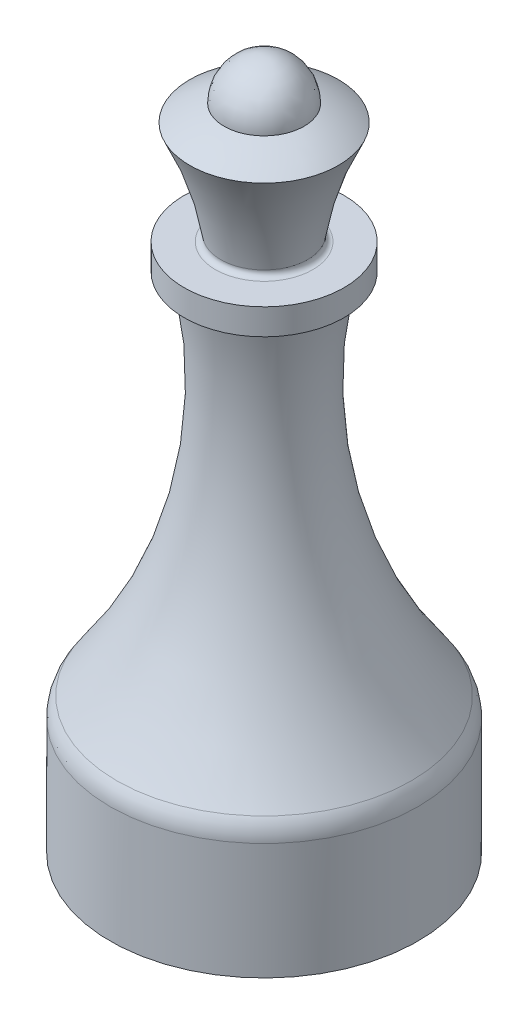
SolidWorks part; units mm, degrees
ref_plane "Front Plane" through (0, 0, 0) normal (0, 0, 1) x (1, 0, 0)
ref_plane "Top Plane" through (0, 0, 0) normal (0, 1, 0) x (1, 0, 0)
ref_plane "Right Plane" through (0, 0, 0) normal (1, 0, 0) x (0, 0, -1)
sketch "Sketch1" plane through (0, 0, 0) normal (0, 0, 1) x (1, 0, 0)
  line L6 (0, 0) -> (14.5, 0)
  line L7 (9.5, 0) -> (9.5, 12)
  line L8 (14.5, 0) -> (14.5, 12)
  line L9 (45.1511, 65) -> (-46.8975, 65) construction
  line L13 (0, 0) -> (0, 65)
  line L14 (8.0064, 17.2031) -> (0, 30)
  line L15 (9.5, 12) -> (14.5, 12) construction
  arc A5 (14.5, 12) -> (6, 46.5615) centre (47.7654, 38.5072) cw
  arc A6 (9.5, 12) -> (8.0064, 17.2031) centre (-0.3099, 12) ccw
  line B0 (6, 46.5615) -> (7.5366, 47.396)
  line B1 (7.5366, 47.396) -> (7.5366, 49.844)
  line B2 (7.5366, 49.844) -> (4.0161, 49.844)
  arc B3 (4.0161, 49.844) -> (7.0059, 59.5593) centre (33.8306, 45.9865) cw
  arc B4 (7.0059, 59.5593) -> (3.7655, 61.1278) centre (-0.4122, 48.3651) ccw
  arc B5 (3.7655, 61.1278) -> (0, 65) centre (-0.0541, 61.1805) ccw
sketch_block_instance "Block1-1"
sketch_block "Block1" parameters "D1"=77.0147, "D2"=9.7796, "D3"=16.8356, "D4"=68, "D5"=5.3, "D6"=92.0485, "D7"=67.9996, "D8"=1.2598
revolve "Revolve2" add sketch "Sketch1" angle 360 about L13
fillet "Fillet1" radius 3 1 edges at (0, 12, -14.5)
fillet "Fillet2" radius 0.5 1 edges at (0, 49.844, -4.0161)
